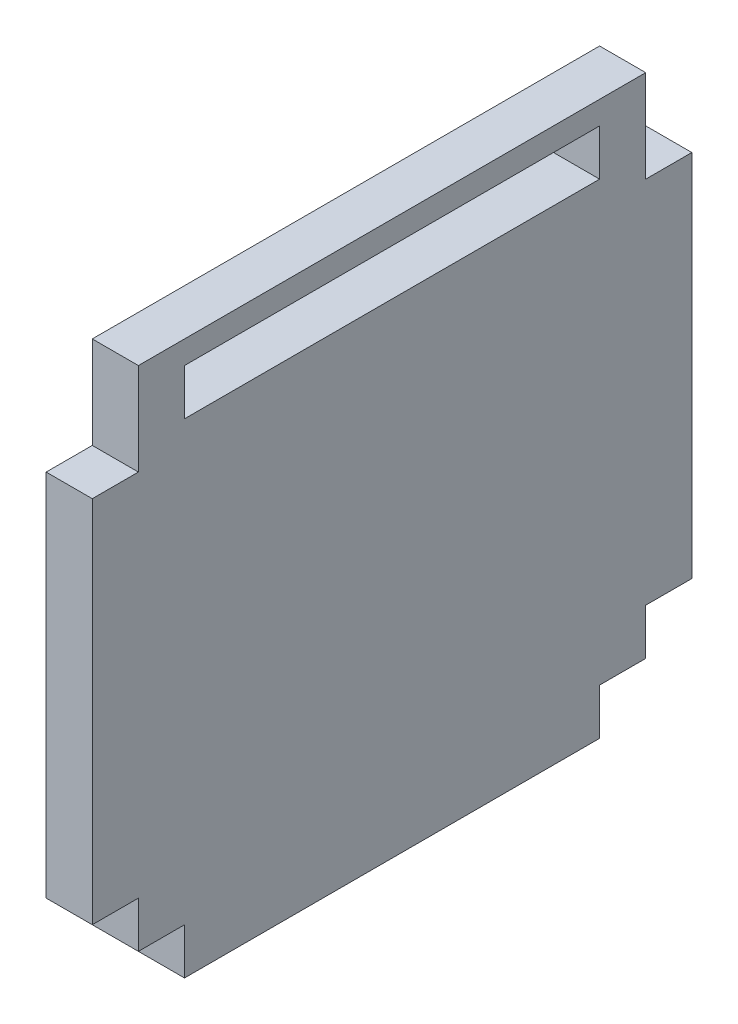
SolidWorks part; units mm, degrees
ref_plane "Front Plane" through (0, 0, 0) normal (0, 0, 1) x (1, 0, 0)
ref_plane "Top Plane" through (0, 0, 0) normal (0, 1, 0) x (1, 0, 0)
ref_plane "Right Plane" through (0, 0, 0) normal (1, 0, 0) x (0, 0, -1)
sketch "Sketch1" plane through (0, 0, 0) normal (0, 0, 1) x (1, 0, 0)
  line L0 (44.45, 38.1) -> (-38.1, 38.1) construction
  line L1 (12.7, 38.1) -> (6.35, 38.1)
  line L2 (12.7, 38.1) -> (12.7, -38.1)
  line L3 (12.7, -38.1) -> (6.35, -38.1)
  line L4 (6.35, 38.1) -> (6.35, -38.1)
  line L5 (-38.1, -38.1) -> (6.35, -38.1) construction
  line L6 (-44.45, 31.75) -> (-44.45, -31.75) construction
  dimension "D1" = 6.35
  dimension "D2" = 50.8
extrude "Boss-Extrude1" add sketch "Sketch1" along normal blind 76.2
sketch "Sketch2" plane through (6.35, 0, 0) normal (-1, 0, 0) x (0, 0, 1)
  line L0 (0, 38.1) -> (0, -38.1) construction
  line L1 (0, -25.4) -> (-6.35, -25.4)
  line L2 (0, -25.4) -> (0, 25.4)
  line L3 (0, 25.4) -> (-6.35, 25.4)
  line L4 (-6.35, -25.4) -> (-6.35, 25.4)
  line L5 (76.2, 38.1) -> (0, 38.1) construction
  line L6 (76.2, -38.1) -> (0, -38.1) construction
  dimension "D1" = 6.35
  dimension "D2" = 12.7
  dimension "D3" = 12.7
extrude "Boss-Extrude2" add sketch "Sketch2" against normal up to surface (6.35 mm away) up to face at (12.7, 0, 38.1)
sketch "Sketch3" plane through (6.35, 0, 0) normal (-1, 0, 0) x (0, 0, 1)
  line L0 (76.2, -31.75) -> (63.5, -31.75) construction
  line L1 (76.2, -38.1) -> (63.5, -38.1)
  line L3 (69.85, -31.75) -> (63.5, -31.75)
  line L4 (63.5, -38.1) -> (63.5, -31.75)
  line L5 (69.85, 25.4) -> (69.85, 38.1) construction
  line L6 (69.85, -25.4) -> (76.2, -25.4)
  line L7 (69.85, -25.4) -> (69.85, -31.75)
  line L8 (69.85, -38.1) -> (76.2, -38.1)
  line L9 (76.2, -25.4) -> (76.2, -38.1)
  line L11 (76.2, 38.1) -> (69.85, 38.1)
  line L12 (76.2, 38.1) -> (76.2, 25.4)
  line L13 (76.2, 25.4) -> (69.85, 25.4)
  line L14 (69.85, 38.1) -> (69.85, 25.4)
  line L15 (0, -38.1) -> (6.35, -38.1)
  line L16 (0, -38.1) -> (0, -31.75)
  line L17 (0, -31.75) -> (6.35, -31.75)
  line L18 (6.35, -38.1) -> (6.35, -31.75)
  line M5 (0, -25.4) -> (0, -38.1)
  line M6 (0, -38.1) -> (76.2, -38.1)
  line M7 (76.2, -38.1) -> (76.2, 38.1)
  dimension "D1" = 12.7
  dimension "D2" = 6.35
extrude "Cut-Extrude1" cut sketch "Sketch3" against normal through all contours L6 L7 L3 L4 L1 M6 M7 | L18 L17 M6 M5 | L12 L13 L14 L11
sketch "Sketch4" plane through (6.35, 0, 0) normal (-1, 0, 0) x (0, 0, 1)
  line L4 (63.5, 34.925) -> (6.35, 34.925)
  line L5 (6.35, 34.925) -> (6.35, 28.575)
  line L6 (6.35, 28.575) -> (63.5, 28.575)
  line L7 (63.5, 28.575) -> (63.5, 34.925)
  line L8 (63.5, 34.925) -> (6.35, 34.925)
  line L9 (6.35, 34.925) -> (6.35, 28.575)
  line L10 (6.35, 28.575) -> (63.5, 28.575)
  line L11 (63.5, 28.575) -> (63.5, 34.925)
  dimension "D1" = 0
extrude "Cut-Extrude2" cut sketch "Sketch4" against normal through all
